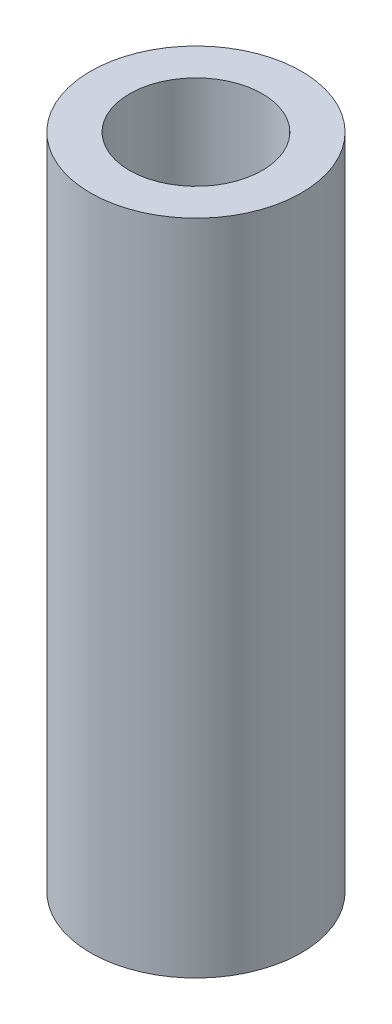
SolidWorks part; units mm, degrees
material "6061-T6 (SS)"
ref_plane "X-Y Datum" through (0, 0, 0) normal (0, 0, 1) x (1, 0, 0)
ref_plane "X-Z Datum" through (0, 0, 0) normal (0, 1, 0) x (1, 0, 0)
ref_plane "Y-Z Datum" through (0, 0, 0) normal (1, 0, 0) x (0, 0, -1)
sketch "Sketch1" plane through (0, 0, 0) normal (0, 1, 0) x (1, 0, 0)
  circle A0 centre (0, 0) radius 3.175
  circle A1 centre (0, 0) radius 2
  dimension "D1" = 6.35
  dimension "D2" = 4
extrude "Boss-Extrude1" add sketch "Sketch1" against normal blind 19.812
